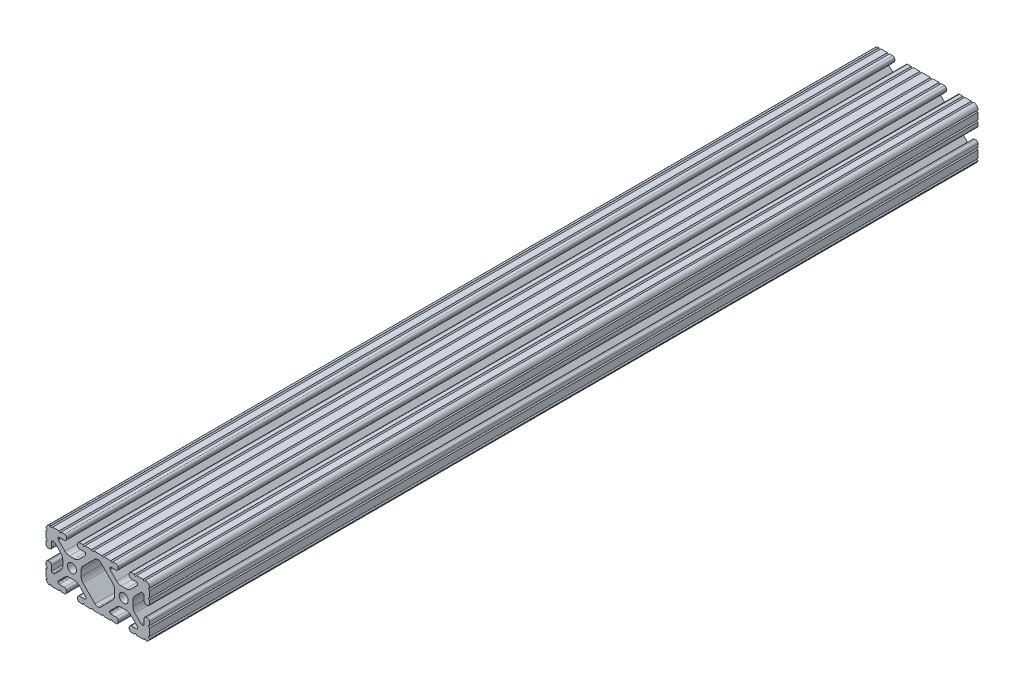
SolidWorks part; units mm, degrees
material "6061 Alloy"
ref_plane "Front Plane" through (0, 0, 0) normal (0, 0, 1) x (1, 0, 0)
ref_plane "Top Plane" through (0, 0, 0) normal (0, 1, 0) x (1, 0, 0)
ref_plane "Right Plane" through (0, 0, 0) normal (1, 0, 0) x (0, 0, -1)
sketch "Sketch1" plane through (0, 0, 0) normal (0, 0, 1) x (1, 0, 0)
  line L0 (-3.1211, -19.05) -> (3.1211, -19.05)
  line L1 (-38.1, 10.287) -> (-38.1, 14.3752)
  line L2 (0, -34.5561) -> (0, 32.8014) construction
  line L3 (-38.1, 0) -> (0, 0) construction
  line L4 (-38.1, 9.5497) -> (-38.1, 10.287)
  line L5 (-19.05, 19.05) -> (-19.05, -20.2827) construction
  line L6 (0, -15.1247) -> (0, -15.1131) construction
  line L7 (9.1761, 12.9058) -> (13.8525, 8.2294)
  line L8 (8.9158, 14.097) -> (8.9158, 13.5344)
  line L9 (13.4112, 14.986) -> (9.8048, 14.986)
  line L10 (14.986, 17.4968) -> (14.986, 16.5608)
  line L11 (10.9975, 19.05) -> (13.4328, 19.05)
  line L12 (8.6331, 19.05) -> (9.4735, 19.05)
  line L13 (4.6451, 19.05) -> (8.6331, 19.05)
  line L14 (31.792, 10.0266) -> (27.1976, 5.4321)
  line L15 (33.147, 10.287) -> (32.4207, 10.287)
  line L16 (29.2071, 19.05) -> (33.2963, 19.05)
  line L17 (28.4698, 19.05) -> (29.2071, 19.05)
  line L18 (-38.1, 5.6388) -> (-38.1, 8.0257)
  line L19 (24.5589, 19.05) -> (26.9458, 19.05)
  line L20 (23.114, 16.5608) -> (23.114, 17.4806)
  line L21 (28.2952, 14.986) -> (24.6888, 14.986)
  line L22 (29.1842, 13.5344) -> (29.1842, 14.097)
  line L23 (-34.036, 9.398) -> (-34.036, 5.6388)
  line L24 (-35.6108, 4.064) -> (-36.5252, 4.064)
  line L25 (24.2475, 8.2294) -> (28.9239, 12.9058)
  line L26 (25.8064, -2.0735) -> (25.8064, 2.0735)
  line L27 (35.6108, 4.064) -> (36.5252, 4.064)
  line L28 (34.036, 9.398) -> (34.036, 5.6388)
  line L29 (38.1, 5.6388) -> (38.1, 8.0257)
  line L30 (38.1, 9.5497) -> (38.1, 10.287)
  line L31 (38.1, 10.287) -> (38.1, 14.3752)
  line L32 (17.2111, 6.8382) -> (20.8889, 6.8382)
  line L33 (2.077, 14.2576) -> (10.9024, 5.4321)
  line L34 (-31.792, -10.0266) -> (-27.1976, -5.4321)
  line L35 (-33.147, -10.287) -> (-32.4207, -10.287)
  line L36 (-29.2071, -19.05) -> (-34.0473, -19.05)
  line L37 (-28.4698, -19.05) -> (-29.2071, -19.05)
  line L38 (-24.6888, -19.05) -> (-26.9458, -19.05)
  line L39 (12.2936, -2.0735) -> (12.2936, 2.0735)
  line L40 (-23.114, -16.5608) -> (-23.114, -17.4752)
  line L41 (-28.448, -14.986) -> (-24.6888, -14.986)
  line L42 (-29.337, -13.6872) -> (-29.337, -14.097)
  line L43 (2.077, -14.2576) -> (10.9024, -5.4321)
  line L44 (-3.1211, 19.05) -> (3.1211, 19.05)
  line L45 (8.763, -14.097) -> (8.763, -13.6872)
  line L46 (-24.2475, -8.2294) -> (-29.0766, -13.0586)
  line L47 (-35.6108, -4.064) -> (-36.5252, -4.064)
  line L48 (-34.036, -9.398) -> (-34.036, -5.6388)
  line L49 (-38.1, -5.6388) -> (-38.1, -8.0257)
  line L50 (-38.1, -9.5497) -> (-38.1, -10.287)
  line L51 (-38.1, -10.287) -> (-38.1, -15.036)
  line L52 (17.2111, -6.8382) -> (20.8889, -6.8382)
  line L53 (38.1, -10.287) -> (38.1, -15.036)
  line L54 (38.1, -9.5497) -> (38.1, -10.287)
  line L55 (38.1, -5.6388) -> (38.1, -8.0257)
  line L56 (34.036, -9.398) -> (34.036, -5.6388)
  line L57 (35.6108, -4.064) -> (36.5252, -4.064)
  line L58 (24.2475, -8.2294) -> (29.0766, -13.0586)
  line L59 (29.337, -13.6872) -> (29.337, -14.097)
  line L60 (-17.2111, -6.8382) -> (-20.8889, -6.8382)
  line L61 (-9.0234, -13.0586) -> (-13.8525, -8.2294)
  line L62 (-8.763, -14.097) -> (-8.763, -13.6872)
  line L63 (-13.4112, -14.986) -> (-9.652, -14.986)
  line L64 (-14.986, -17.4752) -> (-14.986, -16.5608)
  line L65 (-10.9975, -19.05) -> (-13.4112, -19.05)
  line L66 (28.448, -14.986) -> (24.6888, -14.986)
  line L67 (23.114, -16.5608) -> (23.114, -17.4752)
  line L68 (24.6888, -19.05) -> (26.9458, -19.05)
  line L69 (28.4698, -19.05) -> (29.2071, -19.05)
  line L70 (29.2071, -19.05) -> (34.0473, -19.05)
  line L71 (-8.6331, -19.05) -> (-9.4735, -19.05)
  line L72 (33.147, -10.287) -> (32.4207, -10.287)
  line L73 (31.792, -10.0266) -> (27.1976, -5.4321)
  line L74 (-4.6451, -19.05) -> (-8.6331, -19.05)
  line L75 (9.0234, -13.0586) -> (13.8525, -8.2294)
  line L76 (13.4112, -14.986) -> (9.652, -14.986)
  line L77 (-2.077, -14.2576) -> (-10.9024, -5.4321)
  line L78 (14.986, -17.4752) -> (14.986, -16.5608)
  line L79 (10.9975, -19.05) -> (13.4112, -19.05)
  line L80 (4.6451, -19.05) -> (8.6331, -19.05)
  line L81 (8.6331, -19.05) -> (9.4735, -19.05)
  line L83 (-12.2936, -2.0735) -> (-12.2936, 2.0735)
  line L84 (-25.8064, -2.0735) -> (-25.8064, 2.0735)
  line L85 (-2.077, 14.2576) -> (-10.9024, 5.4321)
  line L87 (-4.6451, 19.05) -> (-8.6331, 19.05)
  line L88 (-8.6331, 19.05) -> (-9.4735, 19.05)
  line L89 (-10.9975, 19.05) -> (-13.4328, 19.05)
  line L90 (-14.986, 17.4968) -> (-14.986, 16.5608)
  line L91 (-13.4112, 14.986) -> (-9.8048, 14.986)
  line L92 (-8.9158, 14.097) -> (-8.9158, 13.5344)
  line L93 (-9.1761, 12.9058) -> (-13.8525, 8.2294)
  line L94 (-17.2111, 6.8382) -> (-20.8889, 6.8382)
  line L95 (-24.2475, 8.2294) -> (-28.9239, 12.9058)
  line L96 (-29.1842, 13.5344) -> (-29.1842, 14.097)
  line L97 (-28.2952, 14.986) -> (-24.6888, 14.986)
  line L98 (-23.114, 16.5608) -> (-23.114, 17.4806)
  line L99 (-24.5589, 19.05) -> (-26.9458, 19.05)
  line L100 (-28.4698, 19.05) -> (-29.2071, 19.05)
  line L101 (-29.2071, 19.05) -> (-33.2963, 19.05)
  line L109 (-33.147, 10.287) -> (-32.4207, 10.287)
  line L165 (-31.792, 10.0266) -> (-27.1976, 5.4321)
  arc A0 (-38.1376, 15.8983) -> (-38.1, 14.3752) centre (-38.1, 15.1372) cw
  arc A1 (-38.1, 9.5497) -> (-38.1, 8.0257) centre (-38.1, 8.7877) cw
  arc A2 (9.1761, 12.9058) -> (8.9158, 13.5344) centre (9.8048, 13.5344) cw
  arc A3 (8.9158, 14.097) -> (9.8048, 14.986) centre (9.8048, 14.097) cw
  arc A4 (-36.5252, 4.064) -> (-38.1, 5.6388) centre (-36.5252, 5.6388) cw
  arc A5 (14.986, 16.5608) -> (13.4112, 14.986) centre (13.4112, 16.5608) cw
  arc A6 (13.4328, 19.05) -> (14.986, 17.4968) centre (13.4328, 17.4968) cw
  arc A7 (10.9975, 19.05) -> (9.4735, 19.05) centre (10.2355, 19.05) cw
  arc A8 (4.6451, 19.05) -> (3.1211, 19.05) centre (3.8831, 19.05) cw
  arc A9 (0, 15.1131) -> (2.077, 14.2576) centre (0.0116, 12.1921) cw
  arc A10 (25.8064, 2.0735) -> (27.1976, 5.4321) centre (30.5562, 2.0735) cw
  arc A11 (31.792, 10.0266) -> (32.4207, 10.287) centre (32.4207, 9.398) cw
  arc A12 (33.147, 10.287) -> (34.036, 9.398) centre (33.147, 9.398) cw
  arc A13 (34.8195, 19.0968) -> (38.1376, 15.8983) centre (34.903, 15.8631) cw
  arc A14 (34.8195, 19.0968) -> (33.2963, 19.05) centre (34.0579, 19.0734) cw
  arc A15 (28.4698, 19.05) -> (26.9458, 19.05) centre (27.7078, 19.05) cw
  arc A16 (23.114, 17.4806) -> (24.5589, 19.05) centre (24.6888, 17.4806) cw
  arc A17 (24.6888, 14.986) -> (23.114, 16.5608) centre (24.6888, 16.5608) cw
  arc A18 (28.2952, 14.986) -> (29.1842, 14.097) centre (28.2952, 14.097) cw
  arc A19 (29.1842, 13.5344) -> (28.9239, 12.9058) centre (28.2952, 13.5344) cw
  arc A20 (-35.5713, -19.05) -> (-38.1, -16.56) centre (-34.9455, -15.8855) cw
  arc A21 (34.036, 5.6388) -> (35.6108, 4.064) centre (35.6108, 5.6388) ccw
  arc A22 (36.5252, 4.064) -> (38.1, 5.6388) centre (36.5252, 5.6388) ccw
  arc A23 (38.1, 9.5497) -> (38.1, 8.0257) centre (38.1, 8.7877) ccw
  arc A24 (24.2475, 8.2294) -> (20.8889, 6.8382) centre (20.8889, 11.588) cw
  arc A25 (17.2111, 6.8382) -> (13.8525, 8.2294) centre (17.2111, 11.588) cw
  arc A26 (10.9024, 5.4321) -> (12.2936, 2.0735) centre (7.5438, 2.0735) cw
  arc A27 (0, -15.1131) -> (2.077, -14.2576) centre (0.0116, -12.1921) ccw
  arc A28 (-34.036, 5.6388) -> (-35.6108, 4.064) centre (-35.6108, 5.6388) cw
  arc A29 (-25.8064, -2.0735) -> (-27.1976, -5.4321) centre (-30.5562, -2.0735) cw
  arc A30 (-31.792, -10.0266) -> (-32.4207, -10.287) centre (-32.4207, -9.398) cw
  arc A31 (-33.147, -10.287) -> (-34.036, -9.398) centre (-33.147, -9.398) cw
  arc A33 (-35.5713, -19.05) -> (-34.0473, -19.05) centre (-34.8093, -19.05) cw
  arc A34 (-28.4698, -19.05) -> (-26.9458, -19.05) centre (-27.7078, -19.05) cw
  arc A35 (10.9024, -5.4321) -> (12.2936, -2.0735) centre (7.5438, -2.0735) ccw
  circle A36 centre (19.05, 0) radius 3.3274
  arc A37 (-23.114, -17.4752) -> (-24.6888, -19.05) centre (-24.6888, -17.4752) cw
  arc A38 (-24.6888, -14.986) -> (-23.114, -16.5608) centre (-24.6888, -16.5608) cw
  arc A39 (-28.448, -14.986) -> (-29.337, -14.097) centre (-28.448, -14.097) cw
  arc A40 (-29.337, -13.6872) -> (-29.0766, -13.0586) centre (-28.448, -13.6872) cw
  arc A41 (-24.2475, -8.2294) -> (-20.8889, -6.8382) centre (-20.8889, -11.588) cw
  arc A42 (-34.036, -5.6388) -> (-35.6108, -4.064) centre (-35.6108, -5.6388) ccw
  arc A43 (-36.5252, -4.064) -> (-38.1, -5.6388) centre (-36.5252, -5.6388) ccw
  arc A44 (-38.1, -9.5497) -> (-38.1, -8.0257) centre (-38.1, -8.7877) ccw
  arc A45 (-38.1, -16.56) -> (-38.1, -15.036) centre (-38.1, -15.798) ccw
  arc A46 (38.1, -16.56) -> (38.1, -15.036) centre (38.1, -15.798) cw
  arc A47 (38.1, -9.5497) -> (38.1, -8.0257) centre (38.1, -8.7877) cw
  arc A48 (36.5252, -4.064) -> (38.1, -5.6388) centre (36.5252, -5.6388) cw
  arc A49 (34.036, -5.6388) -> (35.6108, -4.064) centre (35.6108, -5.6388) cw
  arc A50 (24.2475, -8.2294) -> (20.8889, -6.8382) centre (20.8889, -11.588) ccw
  arc A51 (29.337, -13.6872) -> (29.0766, -13.0586) centre (28.448, -13.6872) ccw
  arc A52 (28.448, -14.986) -> (29.337, -14.097) centre (28.448, -14.097) ccw
  arc A53 (24.6888, -14.986) -> (23.114, -16.5608) centre (24.6888, -16.5608) ccw
  arc A54 (-17.2111, -6.8382) -> (-13.8525, -8.2294) centre (-17.2111, -11.588) cw
  arc A55 (-9.0234, -13.0586) -> (-8.763, -13.6872) centre (-9.652, -13.6872) cw
  arc A56 (-8.763, -14.097) -> (-9.652, -14.986) centre (-9.652, -14.097) cw
  arc A57 (-14.986, -16.5608) -> (-13.4112, -14.986) centre (-13.4112, -16.5608) cw
  arc A58 (-13.4112, -19.05) -> (-14.986, -17.4752) centre (-13.4112, -17.4752) cw
  arc A59 (-10.9975, -19.05) -> (-9.4735, -19.05) centre (-10.2355, -19.05) cw
  arc A60 (-4.6451, -19.05) -> (-3.1211, -19.05) centre (-3.8831, -19.05) cw
  arc A61 (23.114, -17.4752) -> (24.6888, -19.05) centre (24.6888, -17.4752) ccw
  arc A62 (28.4698, -19.05) -> (26.9458, -19.05) centre (27.7078, -19.05) ccw
  arc A63 (35.5713, -19.05) -> (34.0473, -19.05) centre (34.8093, -19.05) ccw
  arc A64 (35.5713, -19.05) -> (38.1, -16.56) centre (34.9379, -15.8778) ccw
  arc A65 (33.147, -10.287) -> (34.036, -9.398) centre (33.147, -9.398) ccw
  arc A66 (31.792, -10.0266) -> (32.4207, -10.287) centre (32.4207, -9.398) ccw
  arc A67 (-10.9024, -5.4321) -> (-12.2936, -2.0735) centre (-7.5438, -2.0735) cw
  arc A68 (0, -15.1131) -> (-2.077, -14.2576) centre (-0.0116, -12.1921) cw
  arc A69 (0, 15.1131) -> (-2.077, 14.2576) centre (-0.0116, 12.1921) ccw
  arc A70 (-10.9024, 5.4321) -> (-12.2936, 2.0735) centre (-7.5438, 2.0735) ccw
  arc A71 (25.8064, -2.0735) -> (27.1976, -5.4321) centre (30.5562, -2.0735) ccw
  arc A72 (9.0234, -13.0586) -> (8.763, -13.6872) centre (9.652, -13.6872) ccw
  arc A73 (8.763, -14.097) -> (9.652, -14.986) centre (9.652, -14.097) ccw
  arc A74 (17.2111, -6.8382) -> (13.8525, -8.2294) centre (17.2111, -11.588) ccw
  arc A75 (13.4112, -19.05) -> (14.986, -17.4752) centre (13.4112, -17.4752) ccw
  arc A76 (14.986, -16.5608) -> (13.4112, -14.986) centre (13.4112, -16.5608) ccw
  arc A77 (-4.6451, 19.05) -> (-3.1211, 19.05) centre (-3.8831, 19.05) ccw
  arc A78 (-10.9975, 19.05) -> (-9.4735, 19.05) centre (-10.2355, 19.05) ccw
  arc A79 (-13.4328, 19.05) -> (-14.986, 17.4968) centre (-13.4328, 17.4968) ccw
  arc A80 (-14.986, 16.5608) -> (-13.4112, 14.986) centre (-13.4112, 16.5608) ccw
  arc A81 (-8.9158, 14.097) -> (-9.8048, 14.986) centre (-9.8048, 14.097) ccw
  arc A82 (-9.1761, 12.9058) -> (-8.9158, 13.5344) centre (-9.8048, 13.5344) ccw
  arc A83 (-17.2111, 6.8382) -> (-13.8525, 8.2294) centre (-17.2111, 11.588) ccw
  arc A84 (-24.2475, 8.2294) -> (-20.8889, 6.8382) centre (-20.8889, 11.588) ccw
  arc A85 (-29.1842, 13.5344) -> (-28.9239, 12.9058) centre (-28.2952, 13.5344) ccw
  arc A86 (-28.2952, 14.986) -> (-29.1842, 14.097) centre (-28.2952, 14.097) ccw
  arc A87 (-24.6888, 14.986) -> (-23.114, 16.5608) centre (-24.6888, 16.5608) ccw
  arc A88 (-23.114, 17.4806) -> (-24.5589, 19.05) centre (-24.6888, 17.4806) ccw
  arc A89 (-28.4698, 19.05) -> (-26.9458, 19.05) centre (-27.7078, 19.05) ccw
  arc A90 (-34.8195, 19.0968) -> (-33.2963, 19.05) centre (-34.0579, 19.0734) ccw
  arc A91 (-34.8195, 19.0968) -> (-38.1376, 15.8983) centre (-34.903, 15.8631) ccw
  arc A92 (4.6451, -19.05) -> (3.1211, -19.05) centre (3.8831, -19.05) ccw
  arc A93 (10.9975, -19.05) -> (9.4735, -19.05) centre (10.2355, -19.05) ccw
  arc A94 (38.1376, 15.8983) -> (38.1, 14.3752) centre (38.1, 15.1372) ccw
  arc A96 (-33.147, 10.287) -> (-34.036, 9.398) centre (-33.147, 9.398) ccw
  arc A97 (-31.792, 10.0266) -> (-32.4207, 10.287) centre (-32.4207, 9.398) ccw
  arc A98 (-25.8064, 2.0735) -> (-27.1976, 5.4321) centre (-30.5562, 2.0735) ccw
  circle A101 centre (-19.05, 0) radius 3.3274
  point P34 (0, 19.05)
  point P79 (25.6765, 0)
  point P274 (0, -19.05)
  point P282 (-25.6765, 0)
  point P283 (-12.2936, 0)
  dimension "D1" = 38.1
  dimension "D4" = 6.6548
  dimension "D10" = 4.064
  dimension "D2" = 76.2
  dimension "D3" = 38.1
  dimension "D5" = 8.128
  dimension "D6" = 20.574
  dimension "D7" = 12.2936
  dimension "D8" = 4.064
  dimension "D9" = 4.064
extrude "Extrude1" add sketch "Sketch1" against normal blind 609.6
